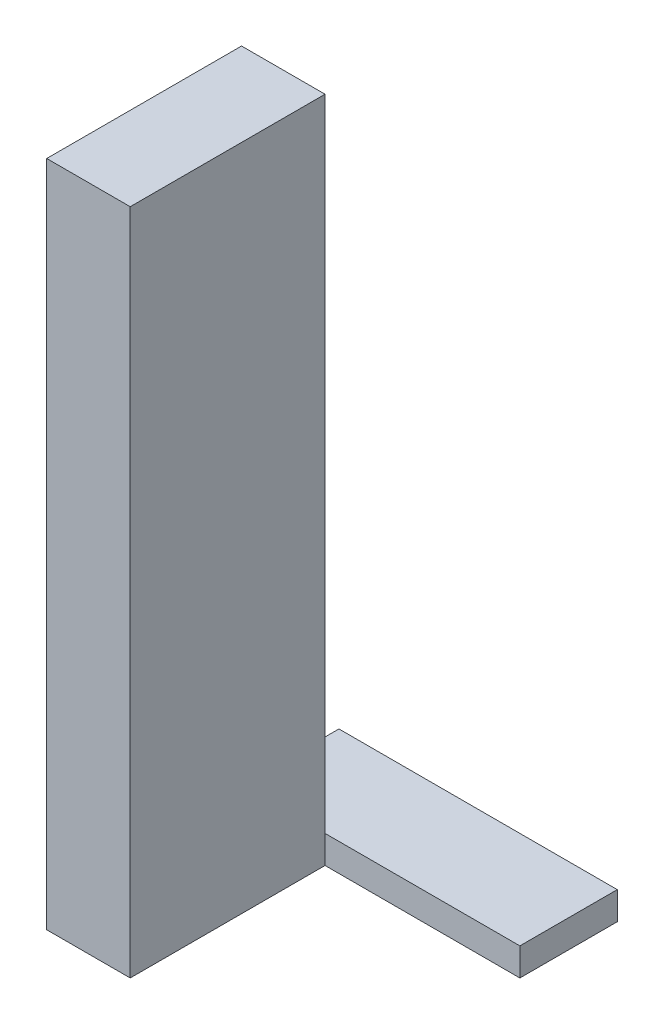
SolidWorks part; units mm, degrees
ref_plane "Front Plane" through (0, 0, 0) normal (0, 0, 1) x (1, 0, 0)
ref_plane "Top Plane" through (0, 0, 0) normal (0, 1, 0) x (1, 0, 0)
ref_plane "Right Plane" through (0, 0, 0) normal (1, 0, 0) x (0, 0, -1)
other "Configuration Table"
sketch "Sketch1" plane through (0, 0, 0) normal (1, 0, 0) x (0, 0, -1)
  line L1 (-484, 390) -> (-512, 390)
  line L2 (-484, 390) -> (-484, 486)
  line L3 (-484, 486) -> (-512, 486)
  line L4 (-512, 390) -> (-512, 486)
  line L5 (-484, 390) -> (-512, 486) construction
  line L6 (-484, 486) -> (-512, 390) construction
  point P0 (-498, 438)
extrude "upright" add sketch "Sketch1" along normal blind 12 from offset 0 separate body
sketch "Sketch2" plane through (0, 0, 0) normal (1, 0, 0) x (0, 0, -1)
  line L0 (-484, 390) -> (-484, 486) construction
  line L1 (-470, 390) -> (-484, 390)
  line L2 (-470, 390) -> (-470, 394)
  line L3 (-470, 394) -> (-484, 394)
  line L4 (-484, 390) -> (-484, 394)
  line L5 (-470, 390) -> (-484, 394) construction
  line L6 (-470, 394) -> (-484, 390) construction
  point P0 (-477, 392)
extrude "foot" add sketch "Sketch2" along normal blind 40 from offset 0 separate body
